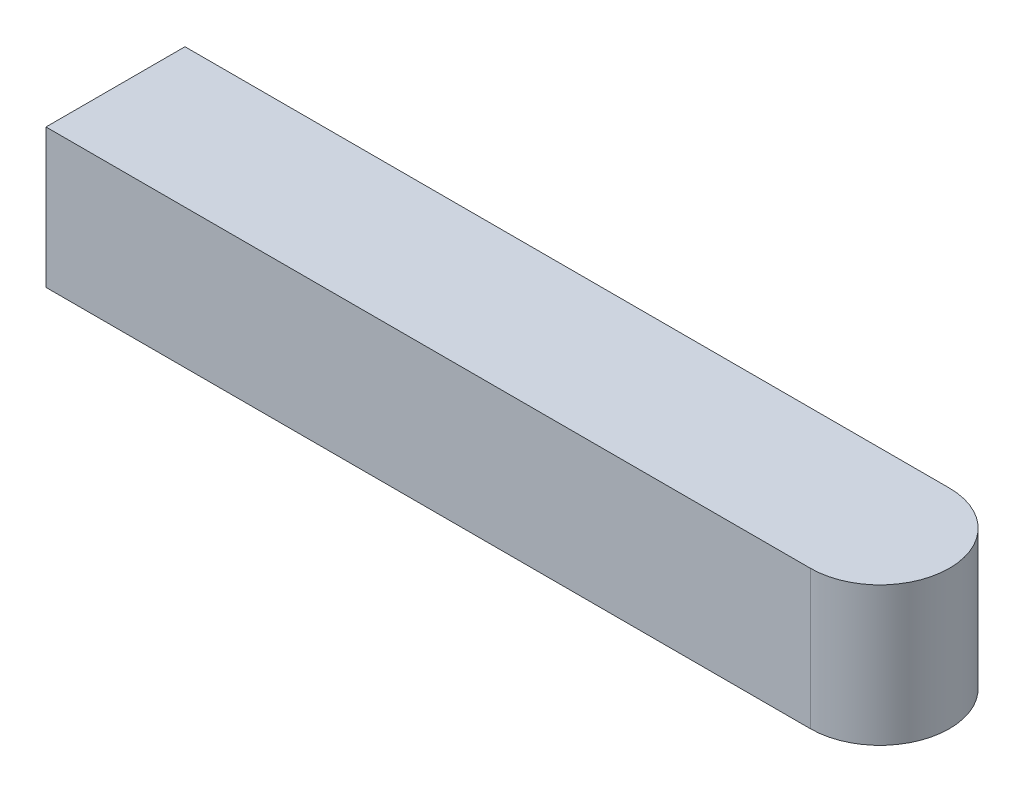
SolidWorks part; units mm, degrees
material "1.4401 (X5CrNiMo17-12-2)"
ref_plane "正面" through (0, 0, 0) normal (0, 0, 1) x (1, 0, 0)
ref_plane "平面" through (0, 0, 0) normal (0, 1, 0) x (1, 0, 0)
ref_plane "右側面" through (0, 0, 0) normal (1, 0, 0) x (0, 0, -1)
sketch "ｽｹｯﾁ1" plane through (0, 0, 0) normal (0, 1, 0) x (1, 0, 0)
  line L0 (-13.75, 0) -> (13.75, 0) construction
  line L1 (-13.75, 2.5) -> (13.75, 2.5)
  line L2 (-13.75, -2.5) -> (13.75, -2.5)
  line L3 (-13.75, 2.5) -> (-13.75, -2.5)
  arc A1 (13.75, -2.5) -> (13.75, 2.5) centre (13.75, 0) ccw
  point P2 (0, 0)
  dimension "D2" = 30
  dimension "D1" = 5
extrude "ﾎﾞｽ - 押し出し1" add sketch "ｽｹｯﾁ1" along normal mid plane 5
